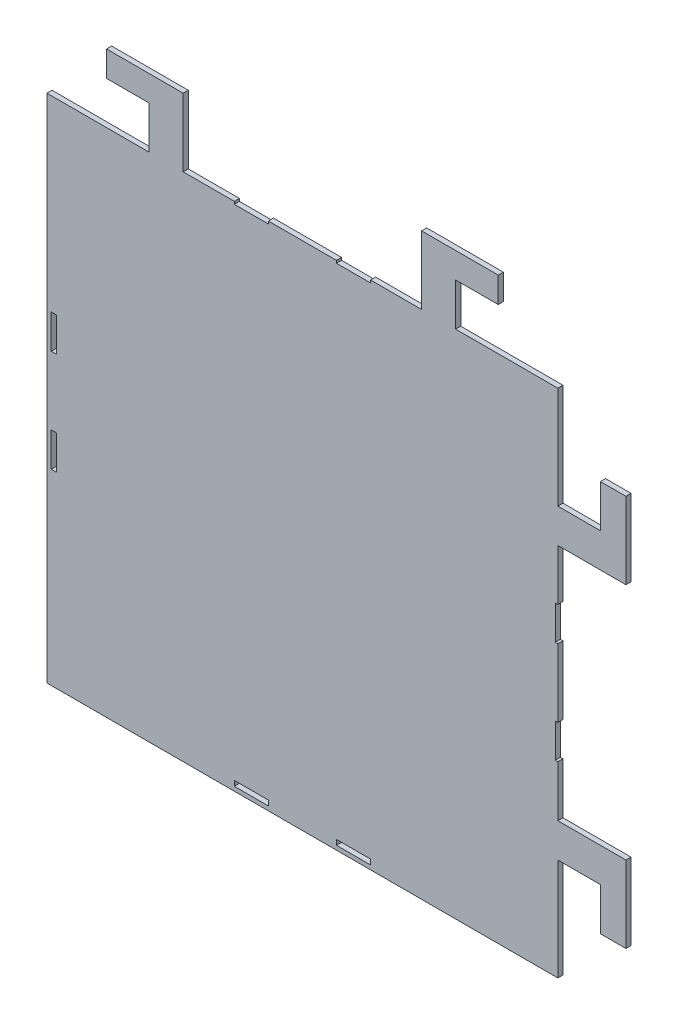
SolidWorks part; units mm, degrees
ref_plane "Plano frontal" through (0, 0, 0) normal (0, 0, 1) x (1, 0, 0)
ref_plane "Plano superior" through (0, 0, 0) normal (0, 1, 0) x (1, 0, 0)
ref_plane "Plano direito" through (0, 0, 0) normal (1, 0, 0) x (0, 0, -1)
sketch "Esboço1" plane through (0, 0, 0) normal (0, 0, 1) x (1, 0, 0)
  line L0 (208.9012, 291.5369) -> (233.9012, 291.5369)
  line L1 (233.9012, 291.5369) -> (233.9012, 306.5369)
  line L2 (233.9012, 306.5369) -> (188.9012, 306.5369)
  line L3 (268.9012, 76.5369) -> (267.4012, 76.5369)
  line L4 (267.4012, 76.5369) -> (267.4012, 96.5369)
  line L5 (267.4012, 96.5369) -> (268.9012, 96.5369)
  line L6 (268.9012, 136.5369) -> (267.4012, 136.5369)
  line L7 (267.4012, 136.5369) -> (267.4012, 156.5369)
  line L8 (267.4012, 156.5369) -> (268.9012, 156.5369)
  line L9 (188.9012, 306.5369) -> (188.9012, 266.5369)
  line L10 (48.9012, 266.5369) -> (48.9012, 306.5369)
  line L11 (48.9012, 306.5369) -> (3.9012, 306.5369)
  line L12 (28.9012, 291.5369) -> (3.9012, 291.5369)
  line L13 (3.9012, 291.5369) -> (3.9012, 306.5369)
  line L14 (158.9012, 266.5369) -> (158.9012, 265.0369)
  line L15 (158.9012, 265.0369) -> (138.9012, 265.0369)
  line L16 (138.9012, 265.0369) -> (138.9012, 266.5369)
  line L17 (98.9012, 266.5369) -> (98.9012, 265.0369)
  line L18 (98.9012, 265.0369) -> (78.9012, 265.0369)
  line L19 (78.9012, 265.0369) -> (78.9012, 266.5369)
  line L20 (28.9012, 291.5369) -> (28.9012, 266.5369)
  line L22 (98.9012, -30.9631) -> (98.9012, -27.9631)
  line L23 (98.9012, -27.9631) -> (78.9012, -27.9631)
  line L24 (78.9012, -27.9631) -> (78.9012, -30.9631)
  line L25 (78.9012, -30.9631) -> (98.9012, -30.9631)
  line L26 (138.9012, -30.9631) -> (158.9012, -30.9631)
  line L27 (158.9012, -30.9631) -> (158.9012, -27.9631)
  line L28 (158.9012, -27.9631) -> (138.9012, -27.9631)
  line L29 (138.9012, -27.9631) -> (138.9012, -30.9631)
  line L30 (-25.5988, 136.5369) -> (-25.5988, 156.5369)
  line L31 (-25.5988, 156.5369) -> (-28.5988, 156.5369)
  line L32 (-28.5988, 156.5369) -> (-28.5988, 136.5369)
  line L33 (-28.5988, 136.5369) -> (-25.5988, 136.5369)
  line L34 (-25.5988, 96.5369) -> (-28.5988, 96.5369)
  line L35 (-28.5988, 96.5369) -> (-28.5988, 76.5369)
  line L36 (-28.5988, 76.5369) -> (-25.5988, 76.5369)
  line L37 (-25.5988, 76.5369) -> (-25.5988, 96.5369)
  line L38 (78.9012, 266.5369) -> (48.9012, 266.5369)
  line L39 (268.9012, 206.5369) -> (268.9012, 266.5369)
  line L40 (293.9012, 206.5369) -> (268.9012, 206.5369)
  line L41 (293.9012, 231.5369) -> (293.9012, 206.5369)
  line L42 (308.9012, 231.5369) -> (293.9012, 231.5369)
  line L43 (308.9012, 186.5369) -> (308.9012, 231.5369)
  line L44 (268.9012, 186.5369) -> (308.9012, 186.5369)
  line L45 (268.9012, 156.5369) -> (268.9012, 186.5369)
  line L46 (308.9012, 46.5369) -> (268.9012, 46.5369)
  line L47 (308.9012, 1.5369) -> (308.9012, 46.5369)
  line L48 (293.9012, 1.5369) -> (308.9012, 1.5369)
  line L49 (293.9012, 26.5369) -> (293.9012, 1.5369)
  line L50 (268.9012, 26.5369) -> (293.9012, 26.5369)
  line L51 (268.9012, -33.4631) -> (268.9012, 26.5369)
  line L52 (-31.0988, -33.4631) -> (268.9012, -33.4631)
  line L53 (-31.0988, 266.5369) -> (-31.0988, -33.4631)
  line L54 (268.9012, 96.5369) -> (268.9012, 136.5369)
  line L55 (208.9012, 266.5369) -> (268.9012, 266.5369)
  line L56 (138.9012, 266.5369) -> (98.9012, 266.5369)
  line L57 (268.9012, 46.5369) -> (268.9012, 76.5369)
  line L58 (28.9012, 266.5369) -> (-31.0988, 266.5369)
  line L59 (188.9012, 266.5369) -> (158.9012, 266.5369)
  line L60 (208.9012, 266.5369) -> (208.9012, 291.5369)
  dimension "D1" = 300
  dimension "D4" = 110
  dimension "D5" = 110
  dimension "D6" = 60
  dimension "D7" = 25
  dimension "D8" = 40
  dimension "D9" = 25
  dimension "D10" = 45
  dimension "D11" = 25
  dimension "D12" = 1.5
  dimension "D13" = 1.5
  dimension "D14" = 30
  dimension "D16" = 40
  dimension "D18" = 30
  dimension "D21" = 15
  dimension "D22" = 40
  dimension "D25" = 60
  dimension "D27" = 300
  dimension "D28" = 2.5
  dimension "D29" = 3
  dimension "D30" = 40
  dimension "D31" = 3
  dimension "D32" = 110
  dimension "D33" = 110
  dimension "D34" = 2.5
  dimension "D35" = 3
  dimension "D36" = 2.5
  dimension "D37" = 3
  dimension "D38" = 300
  dimension "D39" = 300
  dimension "D40" = 60
  dimension "D41" = 45
  dimension "D42" = 25
  dimension "D43" = 25
  dimension "D44" = 30
  dimension "D46" = 40
  dimension "D48" = 30
  dimension "D49" = 60
  dimension "D50" = 25
  dimension "D51" = 45
  dimension "D52" = 15
  dimension "D53" = 40
  dimension "D54" = 2.5
  dimension "D55" = 40
  dimension "D56" = 45
  dimension "D57" = 25
  dimension "D58" = 15
extrude "Ressalto-extrusão1" add sketch "Esboço1" along normal blind 3
